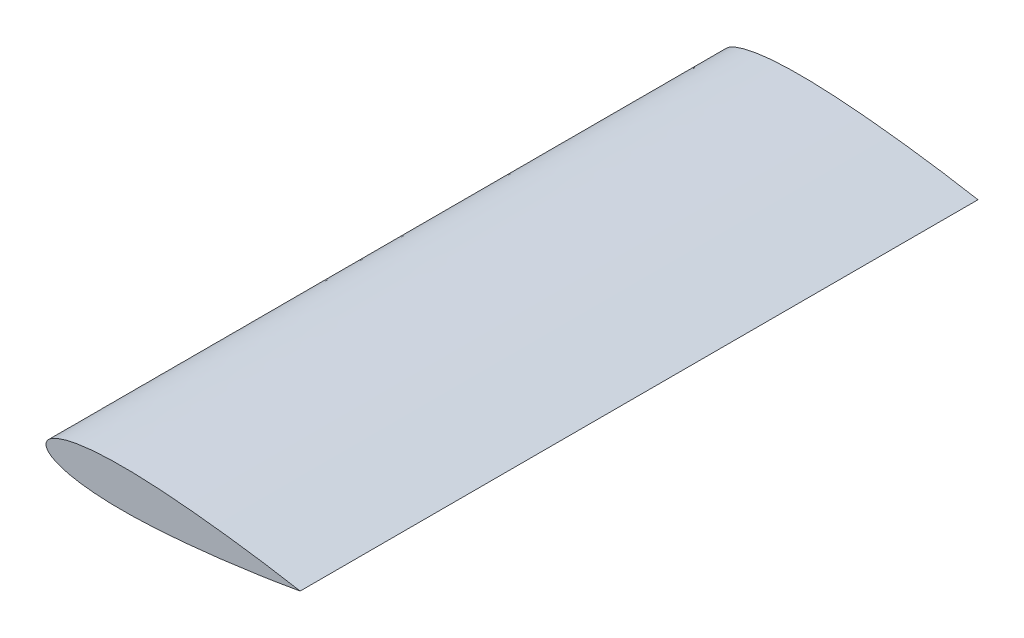
SolidWorks part; units mm, degrees
ref_plane "前视基准面" through (0, 0, 0) normal (0, 0, 1) x (1, 0, 0)
ref_plane "上视基准面" through (0, 0, 0) normal (0, 1, 0) x (1, 0, 0)
ref_plane "右视基准面" through (0, 0, 0) normal (1, 0, 0) x (0, 0, -1)
other "质心 (COM)"
sketch "草图2" plane through (0, 0, 0) normal (0, 0, 1) x (1, 0, 0)
  line L0 (0, 0) -> (300, 0) construction
  spline S0 degree 4 poles (0, 0) (-0.0001, -0.3264) (0.031, -0.854) (0.1504, -1.6168) (0.4487, -2.6089) (0.8484, -3.53) (1.4338, -4.5344) (2.2636, -5.6397) (3.4568, -6.8967) (5.2259, -8.3759) (7.9066, -10.1418) (11.9899, -12.2256) (18.3217, -14.6656) (27.8261, -17.3002) (41.9741, -19.921) (60.222, -21.8105) (78.6241, -22.5522) (95.989, -22.5497) (113.3459, -22.1022) (130.6895, -21.2711) (148.0103, -20.055) (165.3063, -18.538) (179.7033, -17.1021) (191.211, -15.8592) (201.272, -14.6957) (209.8891, -13.6473) (217.0668, -12.7405) (222.8049, -11.9958) (229.9776, -11.0404) (238.5739, -9.8566) (248.6055, -8.4182) (258.6114, -6.9148) (267.2017, -5.5723) (274.3229, -4.4249) (280.0727, -3.4754) (285.7008, -2.5255) (290.8293, -1.6369) (294.8732, -0.9241) (299.0931, -0.1658) (301.6957, 0.3078) (305.9109, 1.0842) (309.2256, 1.7092) (313.2454, 2.4742) (316.8292, 3.1721) (320.6864, 3.9322) (324.3505, 4.6701) (327.2182, 5.2551) (329.0543, 5.6359) (330.002, 5.8328) knots 0 0 0 0 0 0.003841 0.006235 0.009072 0.012193 0.015657 0.019917 0.025339 0.032593 0.042799 0.057705 0.079311 0.112503 0.158973 0.227236 0.2955 0.329632 0.363764 0.432028 0.500292 0.534424 0.568556 0.602688 0.63682 0.653886 0.670952 0.688018 0.705084 0.739215 0.773347 0.807479 0.824545 0.841611 0.858677 0.875743 0.892809 0.901342 0.909875 0.921141 0.932406 0.943672 0.954938 0.966203 0.977469 0.988734 1 1 1 1 1 construction
  spline S1 degree 4 poles (0, 0) (-0.0001, -0.3264) (0.031, -0.854) (0.1504, -1.6168) (0.4487, -2.6089) (0.8484, -3.53) (1.4338, -4.5344) (2.2636, -5.6397) (3.4568, -6.8967) (5.2259, -8.3759) (7.9066, -10.1418) (11.9899, -12.2256) (18.3217, -14.6656) (27.8261, -17.3002) (41.9741, -19.921) (60.222, -21.8105) (78.6241, -22.5522) (95.989, -22.5497) (113.3459, -22.1022) (130.6895, -21.2711) (148.0103, -20.055) (165.3063, -18.538) (179.7033, -17.1021) (191.211, -15.8592) (201.272, -14.6957) (209.8891, -13.6473) (217.0668, -12.7405) (222.8049, -11.9958) (229.9776, -11.0404) (238.5739, -9.8566) (248.6055, -8.4182) (258.6114, -6.9148) (267.2017, -5.5723) (274.3229, -4.4249) (280.0727, -3.4754) (285.7008, -2.5255) (290.8293, -1.6369) (294.8732, -0.9241) (298.0459, -0.354) (299.3524, -0.1177) (300, 0) knots 0 0 0 0 0 0.003841 0.006235 0.009072 0.012193 0.015657 0.019917 0.025339 0.032593 0.042799 0.057705 0.079311 0.112503 0.158973 0.227236 0.2955 0.329632 0.363764 0.432028 0.500292 0.534424 0.568556 0.602688 0.63682 0.653886 0.670952 0.688018 0.705084 0.739215 0.773347 0.807479 0.824545 0.841611 0.858677 0.875743 0.892809 0.901342 0.909875 0.909875 0.909875 0.909875 0.909875
  spline S2 degree 4 poles (0, 0) (-0.0001, 0.3264) (0.031, 0.854) (0.1504, 1.6168) (0.4487, 2.6089) (0.8484, 3.53) (1.4338, 4.5344) (2.2636, 5.6397) (3.4568, 6.8967) (5.2259, 8.3759) (7.9066, 10.1418) (11.9899, 12.2256) (18.3217, 14.6656) (27.8261, 17.3002) (41.9741, 19.921) (60.222, 21.8105) (78.6241, 22.5522) (95.989, 22.5497) (113.3459, 22.1022) (130.6895, 21.2711) (148.0103, 20.055) (165.3063, 18.538) (179.7033, 17.1021) (191.211, 15.8592) (201.272, 14.6957) (209.8891, 13.6473) (217.0668, 12.7405) (222.8049, 11.9958) (229.9776, 11.0404) (238.5739, 9.8566) (248.6055, 8.4182) (258.6114, 6.9148) (267.2017, 5.5723) (274.3229, 4.4249) (280.0727, 3.4754) (285.7008, 2.5255) (290.8293, 1.6369) (294.8732, 0.9241) (298.0459, 0.354) (299.3524, 0.1177) (300, 0) knots 0 0 0 0 0 0.003841 0.006235 0.009072 0.012193 0.015657 0.019917 0.025339 0.032593 0.042799 0.057705 0.079311 0.112503 0.158973 0.227236 0.2955 0.329632 0.363764 0.432028 0.500292 0.534424 0.568556 0.602688 0.63682 0.653886 0.670952 0.688018 0.705084 0.739215 0.773347 0.807479 0.824545 0.841611 0.858677 0.875743 0.892809 0.901342 0.909875 0.909875 0.909875 0.909875 0.909875
extrude "凸台-拉伸1" add sketch "草图2" along normal blind 800
